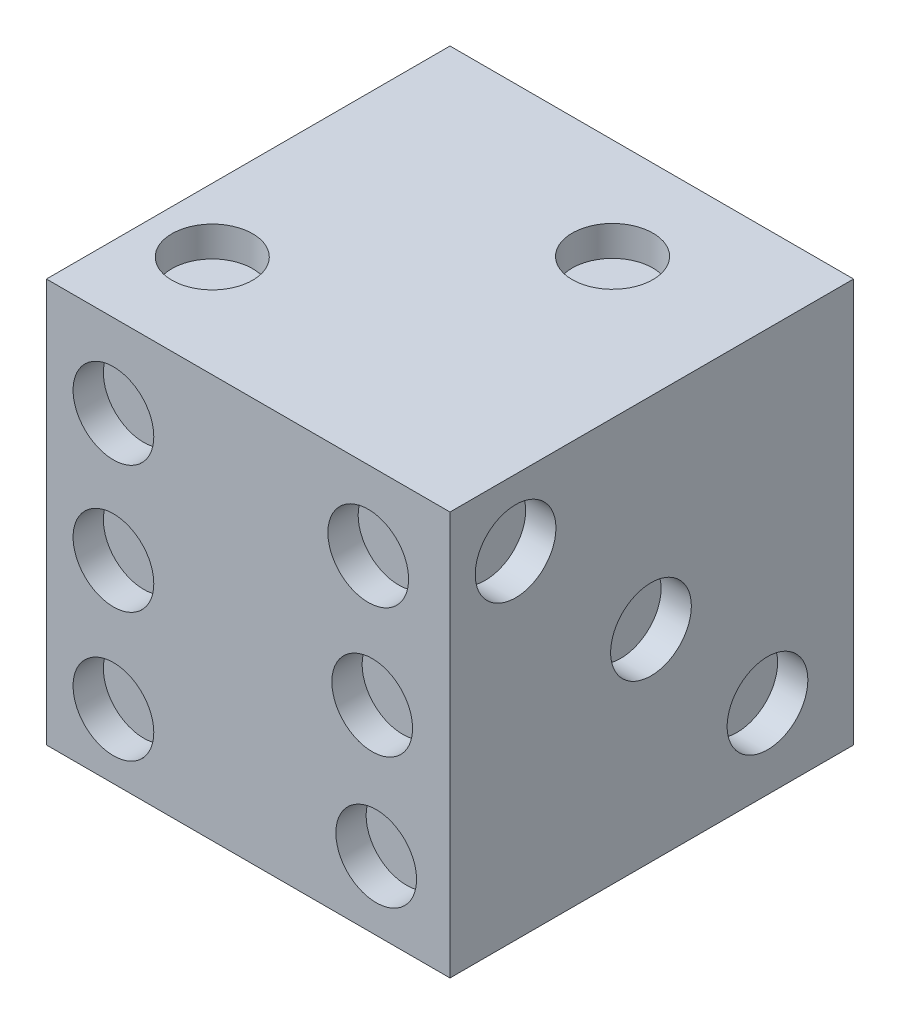
SolidWorks part; units mm, degrees
material "Silicon Rubber"
ref_plane "Front" through (0, 0, 0) normal (0, 0, 1) x (1, 0, 0)
ref_plane "Top" through (0, 0, 0) normal (0, 1, 0) x (1, 0, 0)
ref_plane "Right" through (0, 0, 0) normal (1, 0, 0) x (0, 0, -1)
sketch "Sketch2" plane through (0, 0, 0) normal (0, 0, 1) x (1, 0, 0)
  line L1 (-10, 20) -> (10, 20)
  line L2 (-10, 20) -> (-10, 0)
  line L3 (-10, 0) -> (10, 0)
  line L4 (10, 20) -> (10, 0)
  line L5 (-10, 20) -> (10, 0) construction
  line L6 (-10, 0) -> (10, 20) construction
  point P4 (0, 10)
extrude "Boss-Extrude1" add sketch "Sketch2" along normal blind 20
sketch "Sketch3" plane through (0, 0, 0) normal (0, 0, -1) x (-1, 0, 0)
  circle A0 centre (0, 11.3875) radius 2
extrude "Cut-Extrude2" cut sketch "Sketch3" against normal blind 1.5
sketch "Sketch4" plane through (0, 0, 20) normal (0, 0, 1) x (1, 0, 0)
  line L0 (0, -7.5145) -> (-0.5094, 25.2311) construction
  circle A0 centre (-6.6797, 3.1994) radius 2
  circle A1 centre (-6.6797, 9.5857) radius 2
  circle A2 centre (-6.6797, 15.896) radius 2
  circle A3 centre (5.9483, 16.0924) radius 2
  circle A4 centre (6.1446, 9.7852) radius 2
  circle A5 centre (6.3432, 3.402) radius 2
extrude "Cut-Extrude4" cut sketch "Sketch4" against normal blind 1.5
sketch "Sketch5" plane through (0, 0, 0) normal (0, -1, 0) x (1, 0, 0)
  line L0 (0, -4.4369) -> (0, 20.8453) construction
  circle A0 centre (-7.0311, 4.4176) radius 2
  circle A1 centre (-7.0311, 13.243) radius 2
  circle A2 centre (7.0311, 13.243) radius 2
  circle A3 centre (7.0311, 4.4176) radius 2
extrude "Cut-Extrude5" cut sketch "Sketch5" against normal blind 1.5
sketch "Sketch6" plane through (0, 20, 0) normal (0, 1, 0) x (1, 0, 0)
  circle A0 centre (-6.8362, -14.9457) radius 2
  circle A1 centre (3.0563, -5.0006) radius 2
extrude "Cut-Extrude6" cut sketch "Sketch6" against normal blind 1.5
sketch "Sketch7" plane through (-10, 0, 0) normal (-1, 0, 0) x (0, 0, 1)
  line L0 (24.5764, 9.6395) -> (-3.61, 9.6395) construction
  circle A0 centre (15.6647, 3.4279) radius 2
  circle A1 centre (6.5065, 3.4279) radius 2
  circle A2 centre (6.5065, 15.8511) radius 2
  circle A3 centre (15.6647, 15.8511) radius 2
extrude "Cut-Extrude7" cut sketch "Sketch7" against normal blind 1.5
sketch "Sketch8" plane through (-10, 0, 0) normal (-1, 0, 0) x (0, 0, 1)
  circle A0 centre (10.7373, 9.4768) radius 2
extrude "Cut-Extrude8" cut sketch "Sketch8" against normal blind 1.5
sketch "Sketch9" plane through (10, 0, 0) normal (1, 0, 0) x (0, 0, -1)
  circle A0 centre (-16.7499, 16.6914) radius 2
  circle A1 centre (-10.0394, 9.986) radius 2
  circle A2 centre (-4.2653, 3.9259) radius 2
extrude "Cut-Extrude9" cut sketch "Sketch9" against normal blind 1.5
